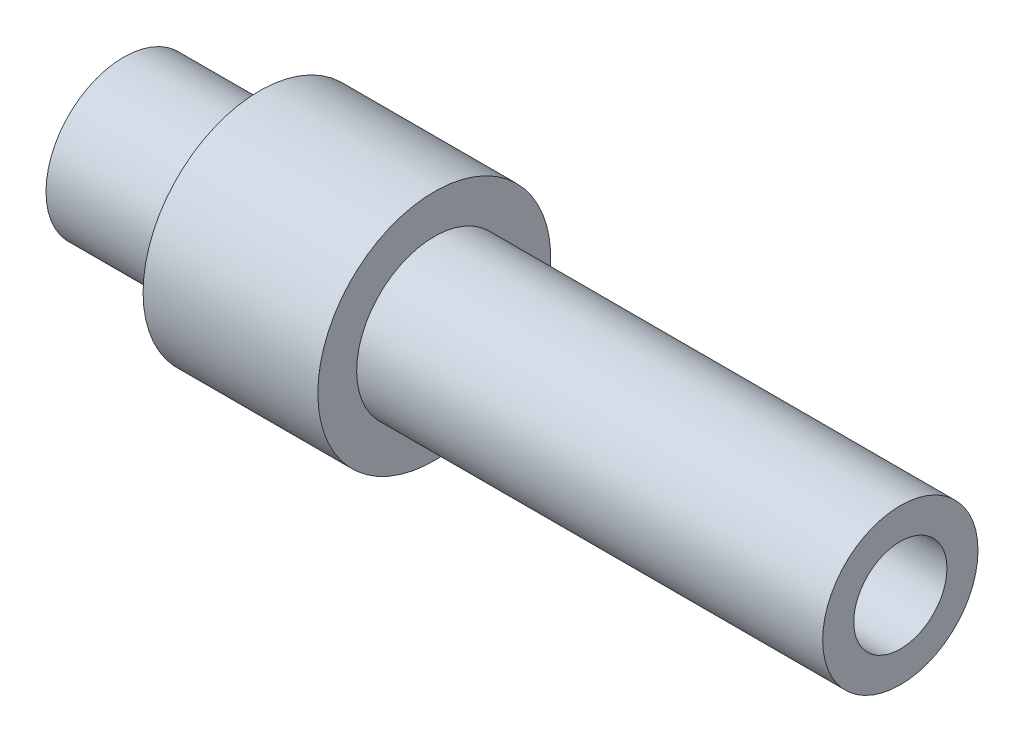
SolidWorks part; units mm, degrees
ref_plane "Front Plane" through (0, 0, 0) normal (0, 0, 1) x (1, 0, 0)
ref_plane "Top Plane" through (0, 0, 0) normal (0, 1, 0) x (1, 0, 0)
ref_plane "Right Plane" through (0, 0, 0) normal (1, 0, 0) x (0, 0, -1)
sketch "Sketch1" plane through (0, 0, 0) normal (1, 0, 0) x (0, 0, -1)
  circle A0 centre (0, 0) radius 4
extrude "Boss-Extrude1" add sketch "Sketch1" along normal blind 40
sketch "Sketch2" plane through (0, 0, 0) normal (-1, 0, 0) x (0, 0, 1)
  circle A0 centre (0, 0) radius 2
  dimension "D1" = 4
extrude "Cut-Extrude1" cut sketch "Sketch2" against normal blind 6
sketch "Sketch3" plane through (0, 0, 0) normal (-1, 0, 0) x (0, 0, 1)
  circle A0 centre (0, 0) radius 2
  circle A1 centre (0, 0) radius 6
  dimension "D1" = 12
extrude "Boss-Extrude2" add sketch "Sketch3" against normal blind 9 from offset 7 offset against normal yes
sketch "Sketch4" plane through (40, 0, 0) normal (1, 0, 0) x (0, 0, -1)
  circle A0 centre (0, 0) radius 2.4
  dimension "D1" = 4.8
extrude "Cut-Extrude2" cut sketch "Sketch4" against normal blind 16
